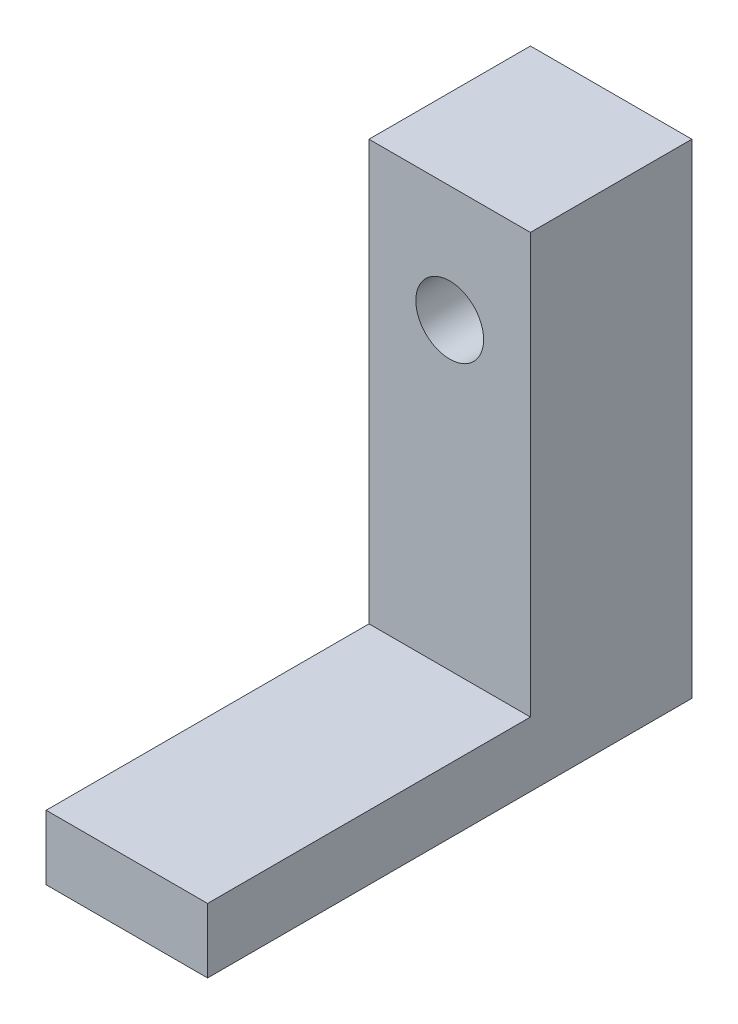
SolidWorks part; units mm, degrees
ref_plane "Front Plane" through (0, 0, 0) normal (0, 0, 1) x (1, 0, 0)
ref_plane "Top Plane" through (0, 0, 0) normal (0, 1, 0) x (1, 0, 0)
ref_plane "Right Plane" through (0, 0, 0) normal (1, 0, 0) x (0, 0, -1)
sketch "Sketch1" plane through (0, 0, 0) normal (0, 0, 1) x (1, 0, 0)
  line L1 (0, 0) -> (5, 0)
  line L2 (0, 0) -> (0, 15)
  line L3 (0, 15) -> (5, 15)
  line L4 (5, 0) -> (5, 15)
  dimension "D1" = 5
  dimension "D2" = 15
extrude "Boss-Extrude1" add sketch "Sketch1" along normal blind 5
sketch "Sketch2" plane through (0, 0, 5) normal (0, 0, 1) x (1, 0, 0)
  line L0 (5, 0) -> (5, 15) construction
  line L1 (0, 0) -> (5, 0)
  line L2 (0, 0) -> (0, 2)
  line L3 (0, 2) -> (5, 2)
  line L4 (5, 0) -> (5, 2)
  dimension "D1" = 2
extrude "Boss-Extrude2" add sketch "Sketch2" along normal blind 10
sketch "Sketch3" plane through (0, 0, 5) normal (0, 0, 1) x (1, 0, 0)
  line L0 (5, 2) -> (5, 15) construction
  line L1 (5, 15) -> (0, 15) construction
  circle A0 centre (2.5, 11.4) radius 1.05
  dimension "D1" = 2.1
  dimension "D2" = 2.5
  dimension "D3" = 3.6
extrude "Cut-Extrude1" cut sketch "Sketch3" against normal blind 10
